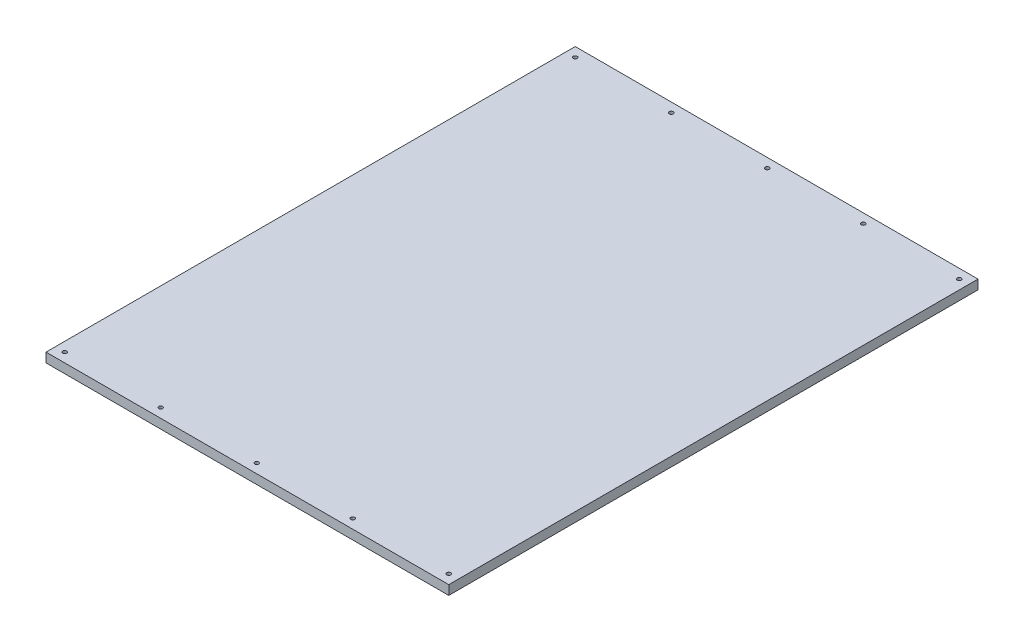
SolidWorks part; units mm, degrees
ref_plane "Front Plane" through (0, 0, 0) normal (0, 0, 1) x (1, 0, 0)
ref_plane "Top Plane" through (0, 0, 0) normal (0, 1, 0) x (1, 0, 0)
ref_plane "Right Plane" through (0, 0, 0) normal (1, 0, 0) x (0, 0, -1)
sketch "Sketch1" plane through (0, 0, 0) normal (0, 1, 0) x (1, 0, 0)
  line L1 (-215, 282.5) -> (215, 282.5)
  line L2 (-215, 282.5) -> (-215, -282.5)
  line L3 (-215, -282.5) -> (215, -282.5)
  line L4 (215, 282.5) -> (215, -282.5)
  line L5 (-215, 282.5) -> (215, -282.5) construction
  line L6 (-215, -282.5) -> (215, 282.5) construction
  point P0 (0, 0)
  dimension "D1" = 565
  dimension "D2" = 430
extrude "Boss-Extrude1" add sketch "Sketch1" along normal blind 10
sketch "Sketch2" plane through (0, 10, 0) normal (0, 1, 0) x (1, 0, 0)
  line L0 (-215, 282.5) -> (-215, 272.5) construction
  line L1 (-215, 282.5) -> (-215, -282.5) construction
  line L2 (-215, 272.5) -> (215, 272.5) construction
  line L3 (-55, 0) -> (55, 0) construction
  circle A0 centre (0, 272.5) radius 2.1
  circle A1 centre (102.5, 272.5) radius 2.1
  circle A2 centre (205, 272.5) radius 2.1
  circle A3 centre (-102.5, 272.5) radius 2.1
  circle A4 centre (-205, 272.5) radius 2.1
  circle A5 centre (205, -272.5) radius 2.1
  circle A6 centre (102.5, -272.5) radius 2.1
  circle A7 centre (0, -272.5) radius 2.1
  circle A8 centre (-102.5, -272.5) radius 2.1
  circle A9 centre (-205, -272.5) radius 2.1
  dimension "D3" = 4.2
  dimension "D4" = 4.2
  dimension "D5" = 4.2
  dimension "D6" = 4.2
  dimension "D7" = 4.2
  dimension "D1" = 10
  dimension "D2" = 430
  dimension "D8" = 10
  dimension "D9" = 102.5
  dimension "D10" = 10
  dimension "D11" = 102.5
extrude "Cut-Extrude1" cut sketch "Sketch2" against normal blind 10
